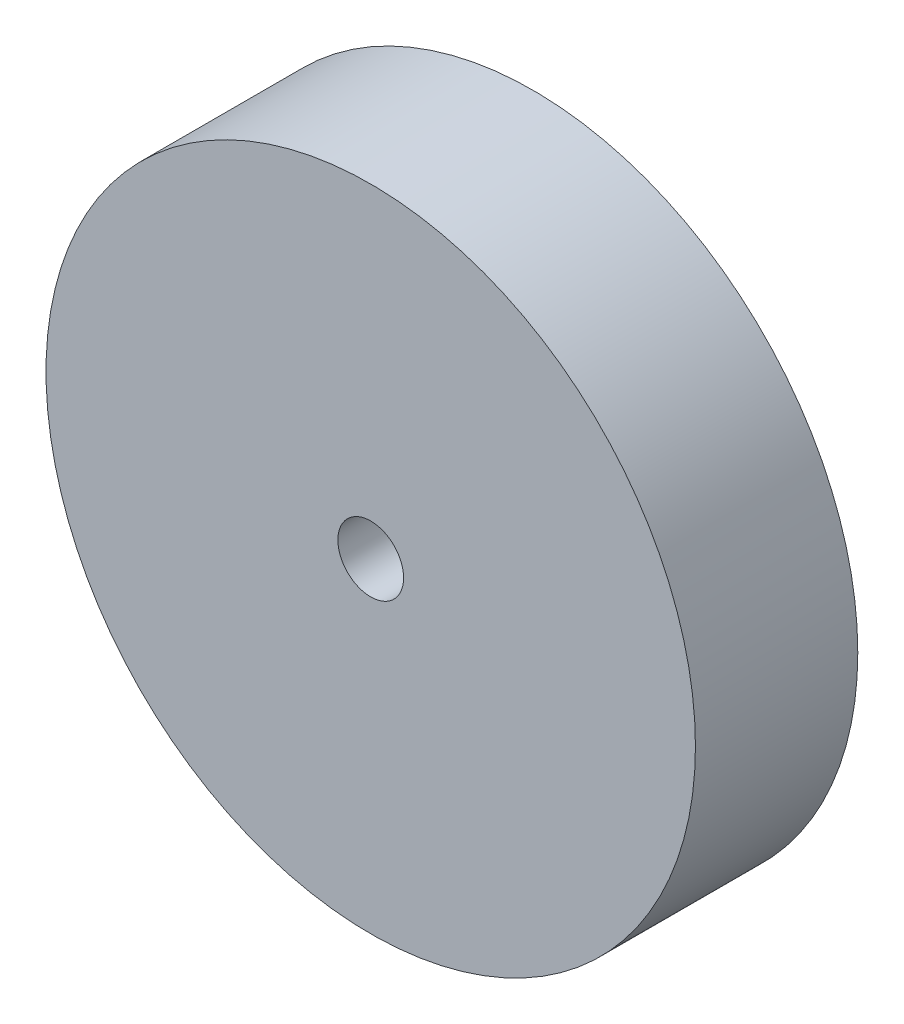
SolidWorks part; units mm, degrees
ref_plane "Alzado" through (0, 0, 0) normal (0, 0, 1) x (1, 0, 0)
ref_plane "Planta" through (0, 0, 0) normal (0, 1, 0) x (1, 0, 0)
ref_plane "Vista lateral" through (0, 0, 0) normal (1, 0, 0) x (0, 0, -1)
sketch "Croquis1" plane through (0, 0, 0) normal (0, 0, 1) x (1, 0, 0)
  circle A0 centre (0, 0) radius 40
  dimension "D1" = 80
extrude "Saliente-Extruir1" add sketch "Croquis1" along normal mid plane 20
sketch "Croquis2" plane through (0, 0, 10) normal (0, 0, 1) x (1, 0, 0)
  circle A0 centre (0, 0) radius 4.05
  dimension "D1" = 8.1
extrude "Cortar-Extruir1" cut sketch "Croquis2" against normal blind 56 and the other way blind 25
